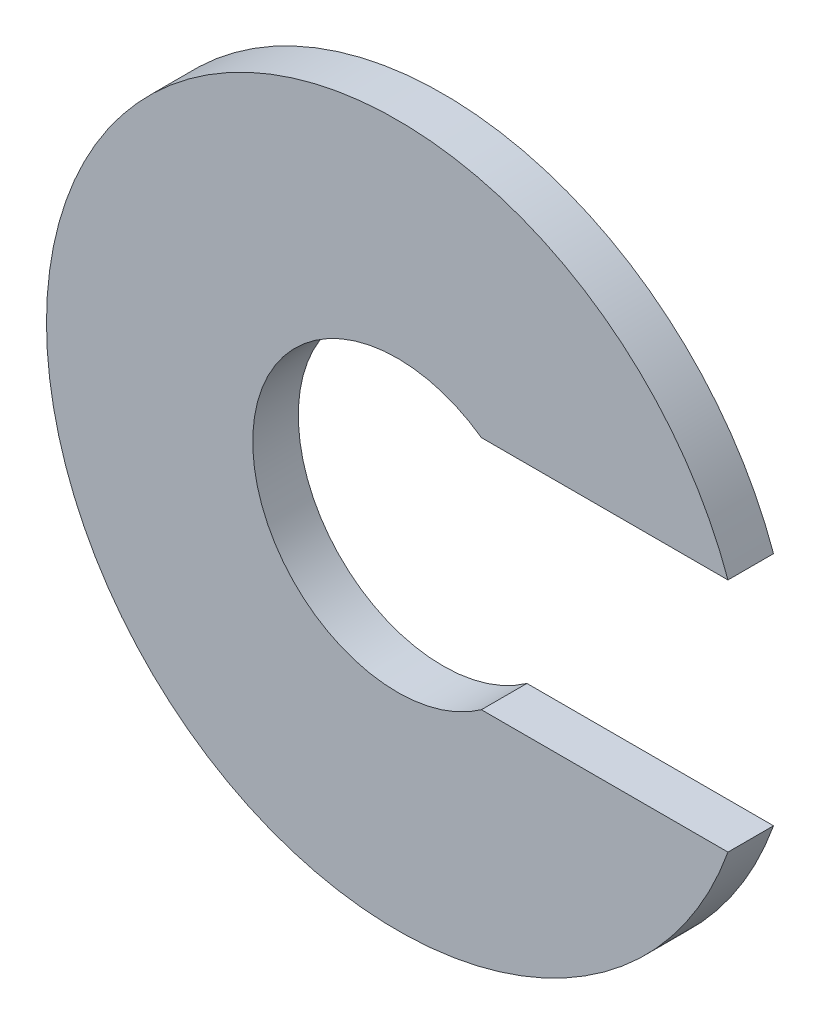
SolidWorks part; units mm, degrees
ref_plane "Plane1" through (0, 0, 0) normal (0, 0, 1) x (1, 0, 0)
ref_plane "Plane2" through (0, 0, 0) normal (0, 1, 0) x (1, 0, 0)
ref_plane "Plane3" through (0, 0, 0) normal (1, 0, 0) x (0, 0, -1)
other "Configuration Table"
sketch "Sketch1" plane through (0, 0, 0) normal (0, 0, 1) x (1, 0, 0)
  line L0 (0, 0) -> (10.06, 0) construction
  line L1 (1.3638, 1.9138) -> (5.3691, 1.9138)
  line L2 (1.3638, -1.9138) -> (5.3691, -1.9138)
  arc A0 (5.3691, 1.9138) -> (5.3691, -1.9138) centre (0, 0) ccw
  arc A1 (1.3638, 1.9138) -> (1.3638, -1.9138) centre (0, 0) ccw
  arc A2 (9.1413, -4.2) -> (9.2011, 4.0674) centre (0, 0) ccw construction
extrude "Base-Extrude" add sketch "Sketch1" along normal up to surface (0.74 mm away)
